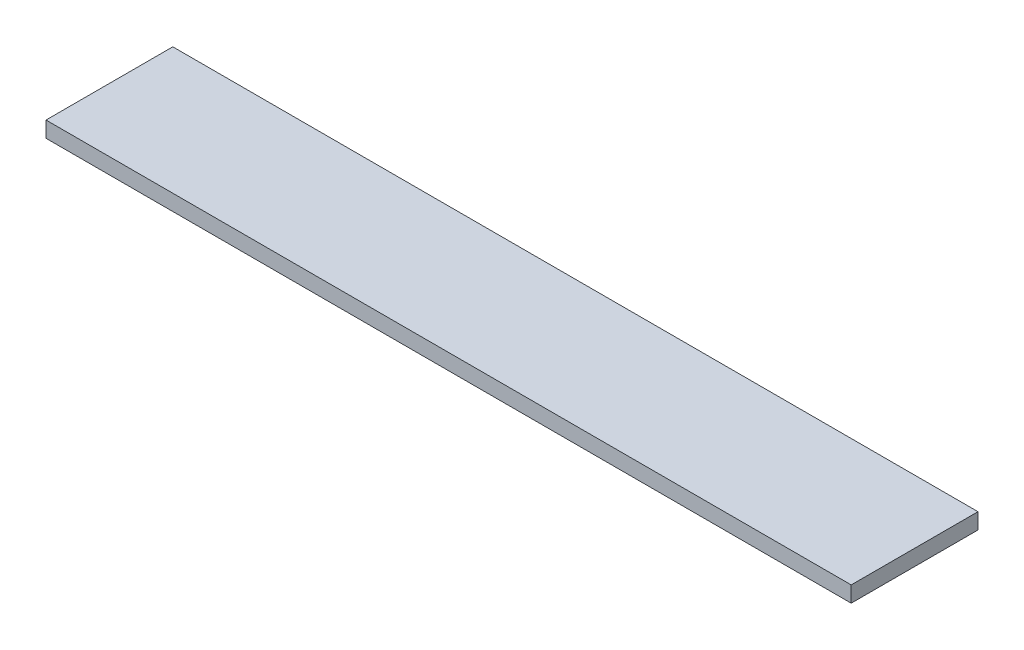
SolidWorks part; units mm, degrees
ref_plane "Front Plane" through (0, 0, 0) normal (0, 0, 1) x (1, 0, 0)
ref_plane "Top Plane" through (0, 0, 0) normal (0, 1, 0) x (1, 0, 0)
ref_plane "Right Plane" through (0, 0, 0) normal (1, 0, 0) x (0, 0, -1)
sketch "Sketch1" plane through (0, 0, 0) normal (0, 1, 0) x (1, 0, 0)
  line L0 (-127, 0) -> (127, 0)
  line L1 (-127, -20) -> (127, -20)
  line L2 (-127, -20) -> (-127, 20)
  line L3 (-127, 20) -> (127, 20)
  line L4 (127, -20) -> (127, 20)
  line L5 (-127, -20) -> (127, 20) construction
  line L6 (-127, 20) -> (127, -20) construction
  point P0 (0, 0)
  dimension "D1" = 254
  dimension "D2" = 40
extrude "Boss-Extrude1" add sketch "Sketch1" along normal blind 5 contours L3 L4 L1 L2
